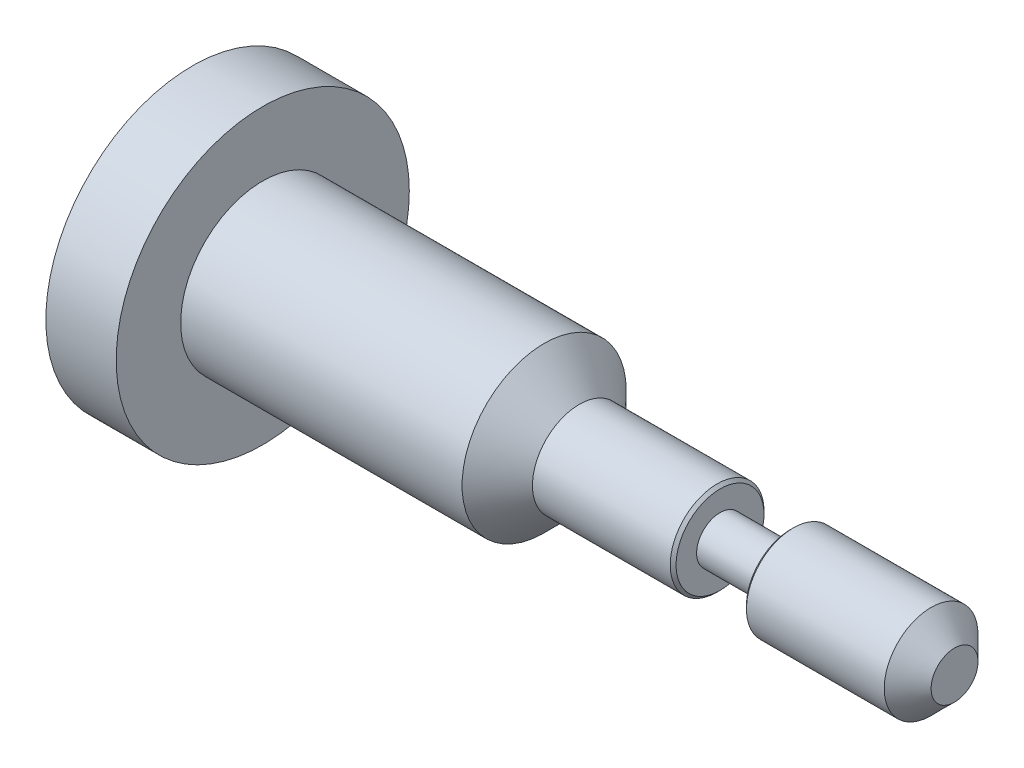
SolidWorks part; units mm, degrees
ref_plane "Ön Düzlem" through (0, 0, 0) normal (0, 0, 1) x (1, 0, 0)
ref_plane "Üst Düzlem" through (0, 0, 0) normal (0, 1, 0) x (1, 0, 0)
ref_plane "Sağ Düzlem" through (0, 0, 0) normal (1, 0, 0) x (0, 0, -1)
sketch "Sketch1" plane through (0, 0, 0) normal (0, 0, 1) x (1, 0, 0)
  line L0 (0, 0) -> (0, 1.5)
  line L1 (0, 1.5) -> (-1.5, 5)
  line L2 (-1.5, 5) -> (-1.5, 6.25)
  line L3 (-1.5, 6.25) -> (1.5, 6.25)
  line L5 (31, 0) -> (0, 0)
  line L6 (1.5, 6.25) -> (1.5, 3.5)
  line L7 (1.5, 3.5) -> (13.5, 3.5)
  line L8 (13.5, 3.5) -> (15, 2)
  line L9 (15, 2) -> (20.875, 2)
  line L10 (21, 1.875) -> (21, 1)
  line L11 (21, 1) -> (24, 1)
  line L12 (24, 1) -> (24, 1.875)
  line L15 (24.125, 2) -> (30, 2)
  line L16 (30, 2) -> (31, 1)
  line L17 (31, 1) -> (31, 0)
  line L19 (20.875, 2) -> (21, 1.875)
  line L20 (24, 1.875) -> (24.125, 2)
  point P6 (1.5, 6.25)
  point P11 (21, 2)
  point P14 (24, 2)
  dimension "D1" = 1.5
  dimension "D2" = 3
  dimension "D3" = 1.25
  dimension "D4" = 1.5
  dimension "D5" = 3.5
  dimension "D6" = 3.5
  dimension "D7" = 12
  dimension "D8" = 1
  dimension "D9" = 135
  dimension "D10" = 1.5
  dimension "D11" = 6
  dimension "D12" = 6
  dimension "D13" = 1
  dimension "D15" = 3
revolve "Revolve1" add sketch "Sketch1" angle 360 about L5
